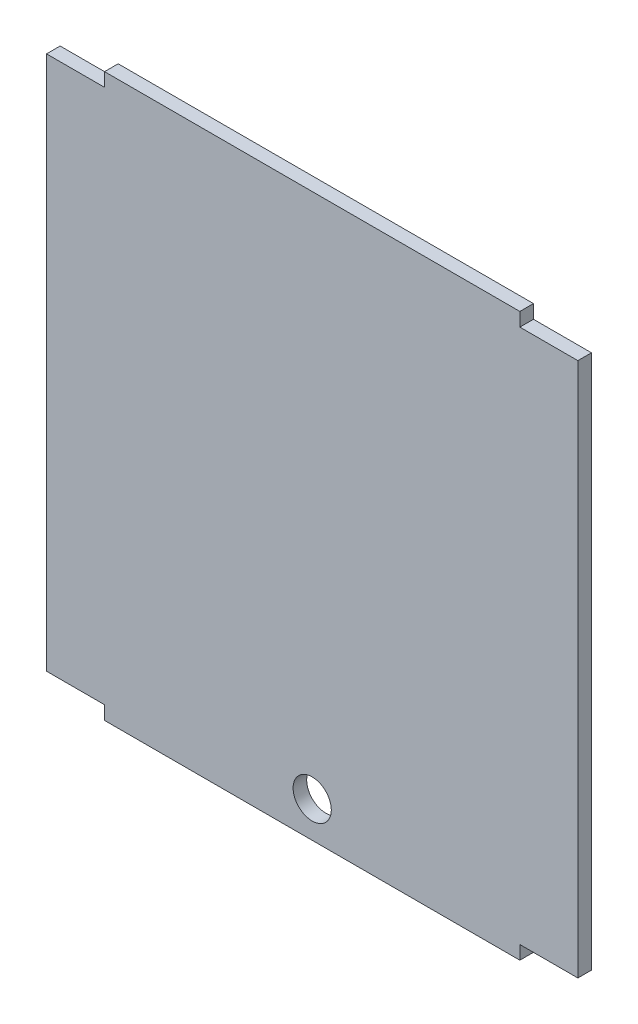
SolidWorks part; units mm, degrees
ref_plane "Front Plane" through (0, 0, 0) normal (0, 0, 1) x (1, 0, 0)
ref_plane "Top Plane" through (0, 0, 0) normal (0, 1, 0) x (1, 0, 0)
ref_plane "Right Plane" through (0, 0, 0) normal (1, 0, 0) x (0, 0, -1)
sketch "Sketch2" plane through (0, 0, 0) normal (0, 0, 1) x (1, 0, 0)
  line L0 (198.3, 224) -> (222.6, 224)
  line L1 (0, 0) -> (24.3, 0)
  line L2 (0, 0) -> (0, 224)
  line L3 (0, 224) -> (24.3, 224)
  line L4 (222.6, 0) -> (222.6, 224)
  line L5 (198.3, 0) -> (222.6, 0)
  line L6 (24.3, 224) -> (24.3, 229.7)
  line L7 (24.3, 229.7) -> (198.3, 229.7)
  line L8 (198.3, 224) -> (198.3, 229.7)
  line L10 (24.3, 0) -> (24.3, -5.7)
  line L11 (24.3, -5.7) -> (198.3, -5.7)
  line L12 (198.3, 0) -> (198.3, -5.7)
  dimension "D1" = 222.6
  dimension "D2" = 224
  dimension "D3" = 5.7
  dimension "D4" = 5.7
  dimension "D5" = 24.3
  dimension "D6" = 24.3
  dimension "D7" = 24.3
  dimension "D8" = 24.3
extrude "Boss-Extrude1" add sketch "Sketch2" along normal blind 5.7
sketch "Sketch3" plane through (0, 0, 5.7) normal (0, 0, 1) x (1, 0, 0)
  line L0 (111.3, -5.7) -> (111.3, 229.7) construction
  line L1 (24.3, -5.7) -> (198.3, -5.7) construction
  line L2 (198.3, 229.7) -> (24.3, 229.7) construction
  circle A0 centre (111.3, 9.3) radius 8
  dimension "D1" = 16
  dimension "D2" = 15
extrude "Cut-Extrude1" cut sketch "Sketch3" against normal blind 5.7
